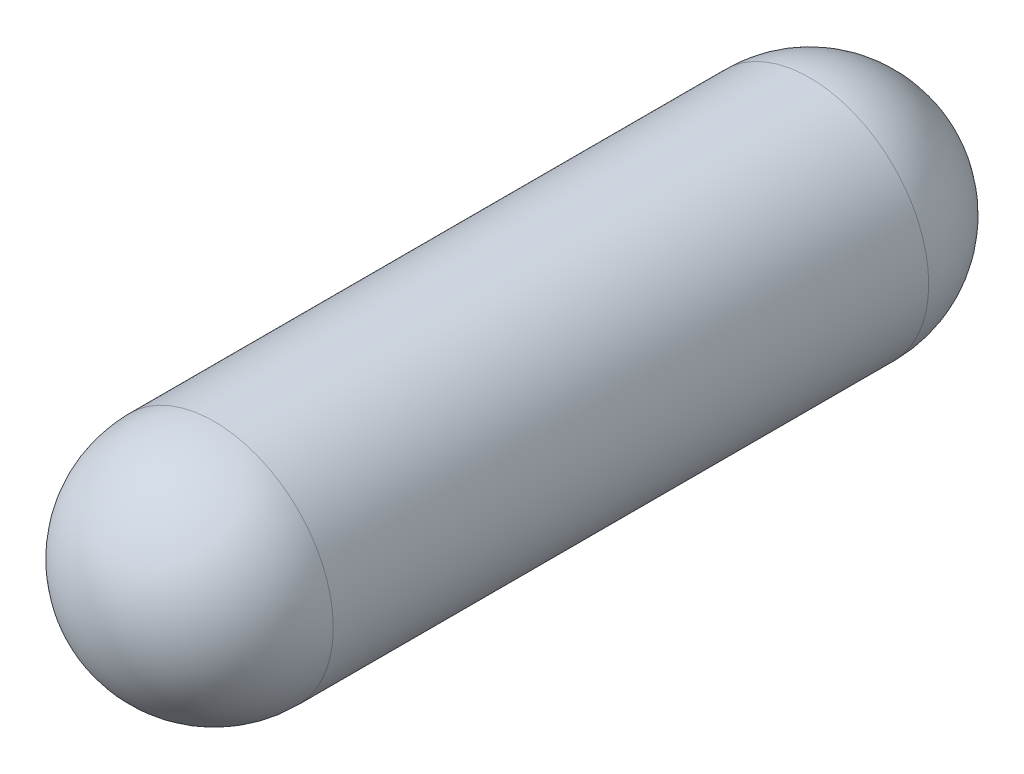
SolidWorks part; units mm, degrees
ref_plane "前视基准面" through (0, 0, 0) normal (0, 0, 1) x (1, 0, 0)
ref_plane "上视基准面" through (0, 0, 0) normal (0, 1, 0) x (1, 0, 0)
ref_plane "右视基准面" through (0, 0, 0) normal (1, 0, 0) x (0, 0, -1)
other "Configuration Table"
sketch "Sketch1" plane through (0, 0, 0) normal (0, 0, 1) x (1, 0, 0)
  circle A0 centre (0, 0) radius 2
  dimension "D1" = 4
extrude "Boss-Extrude1" add sketch "Sketch1" along normal blind 10
sketch "Sketch2" plane through (0, 0, 0) normal (0, 1, 0) x (1, 0, 0)
  line L0 (0, 0) -> (0, -1.1714) construction
  line L1 (0, 2) -> (0, -2)
  line L2 (0, 0) -> (0, -10) construction
  line L3 (-2, -10) -> (2, -10) construction
  line L4 (0, -10) -> (0, -5) construction
  line L5 (0, -5) -> (4.7425, -5) construction
  line L6 (0, -8) -> (0, -12)
  arc A0 (0, -2) -> (0, 2) centre (0, 0) ccw
  arc A1 (0, -8) -> (0, -12) centre (0, -10) cw
revolve "Revolve1" add sketch "Sketch2" angle 360 about L1
